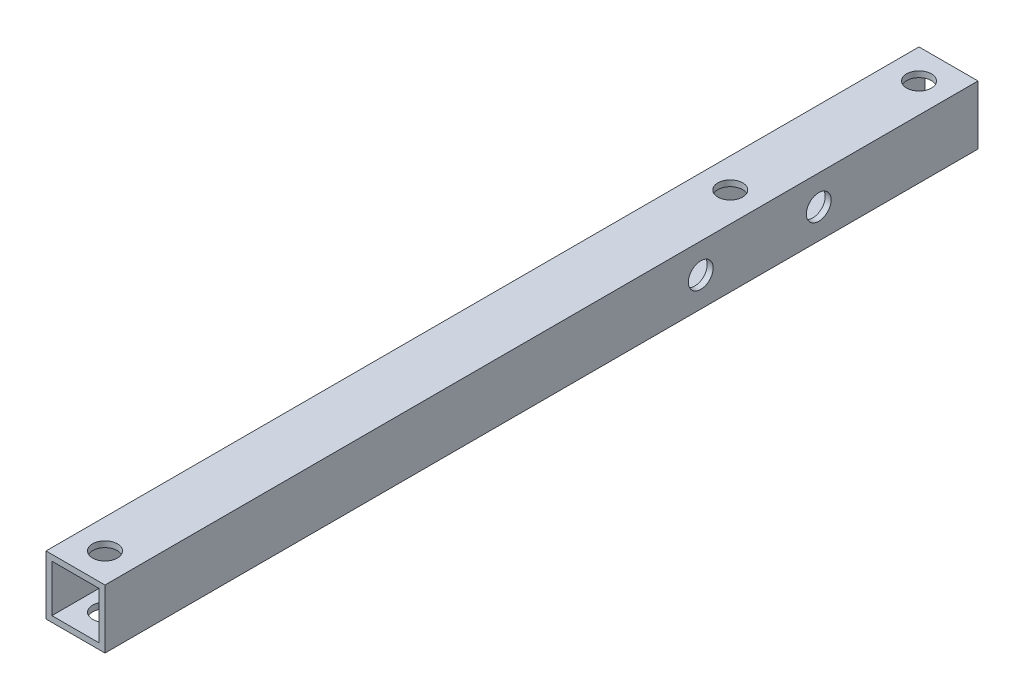
SolidWorks part; units mm, degrees
ref_plane "前视基准面" through (0, 0, 0) normal (0, 0, 1) x (1, 0, 0)
ref_plane "上视基准面" through (0, 0, 0) normal (0, 1, 0) x (1, 0, 0)
ref_plane "右视基准面" through (0, 0, 0) normal (1, 0, 0) x (0, 0, -1)
other "Configuration Table"
sketch "草图1" plane through (0, 0, 0) normal (0, 0, 1) x (1, 0, 0)
  line L1 (0, 0) -> (10, 0)
  line L2 (0, 0) -> (0, -10)
  line L3 (0, -10) -> (10, -10)
  line L4 (10, 0) -> (10, -10)
  dimension "D1" = 10
  dimension "D2" = 10
extrude "拉伸-薄壁1" add sketch "草图1" along normal blind 148 thin
sketch "草图2" plane through (0, 0, 0) normal (-1, 0, 0) x (0, 0, 1)
  line L0 (37, 0) -> (37, -10) construction
  line L1 (148, 0) -> (0, 0) construction
  line L3 (0, 0) -> (0, -10) construction
  circle A0 centre (27, -5) radius 2.1
  circle A1 centre (47, -5) radius 2.1
  point P10 (0, 0)
  point P11 (0, 0)
  dimension "D1" = 4.2
  dimension "D2" = 10
  dimension "D3" = 5
  dimension "D4" = 37
extrude "切除-拉伸1" cut sketch "草图2" against normal through all and the other way through all
sketch "草图3" plane through (0, 0, 0) normal (0, 1, 0) x (1, 0, 0)
  line L0 (0, -74) -> (10, -74) construction
  line L1 (0, -148) -> (0, 0) construction
  line L2 (10, -148) -> (10, 0) construction
  line L3 (5, 0) -> (5, -148) construction
  line L4 (10, 0) -> (0, 0) construction
  line L5 (10, -148) -> (0, -148) construction
  circle A1 centre (5, -5) radius 2.1
  circle A2 centre (5, -143) radius 2.1
  circle A3 centre (5, -37) radius 2.1
  dimension "D1" = 4.2
  dimension "D2" = 4.2
  dimension "D3" = 5
  dimension "D4" = 5
  dimension "D5" = 37
extrude "切除-拉伸2" cut sketch "草图3" against normal through all
